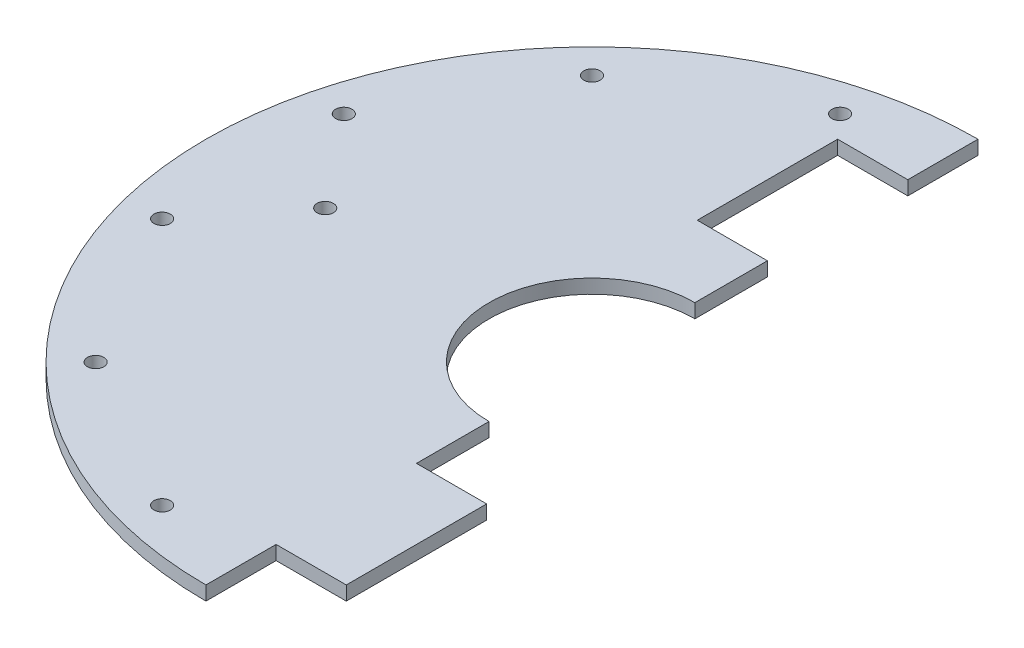
SolidWorks part; units mm, degrees
ref_plane "Front" through (0, 0, 0) normal (0, 0, 1) x (1, 0, 0)
ref_plane "Top" through (0, 0, 0) normal (0, 1, 0) x (1, 0, 0)
ref_plane "Right" through (0, 0, 0) normal (1, 0, 0) x (0, 0, -1)
sketch "Sketch1" plane through (0, 0, 0) normal (0, 1, 0) x (1, 0, 0)
  circle A0 centre (0, 0) radius 82.5
  dimension "D1" = 165
extrude "Boss-Extrude1" add sketch "Sketch1" along normal blind 3
sketch "Sketch2" plane through (0, 3, 0) normal (0, 1, 0) x (1, 0, 0)
  circle A0 centre (57, 0) radius 1.75
  circle A1 centre (0, 0) radius 22
  circle A2 centre (-57, 0) radius 1.75
  dimension "D1" = 3.5
  dimension "D2" = 44
  dimension "D4" = 3.5
  dimension "D3" = 57
  dimension "D5" = 57
extrude "Cut-Extrude1" cut sketch "Sketch2" against normal blind 3
sketch "Sketch3" plane through (0, 3, 0) normal (0, 1, 0) x (1, 0, 0)
  line L0 (0, 0) -> (90.6175, 0) construction
  circle A0 centre (72.4444, -19.4114) radius 1.75
  dimension "D2" = 3.5
  dimension "D1" = 75
  dimension "D3" = 15
extrude "Cut-Extrude2" cut sketch "Sketch3" against normal through all
pattern_circular "CirPattern1" count 12 over 360 about axis through (0, 0, 0) along (0, 1, 0) of "Cut-Extrude2"
sketch "Sketch4" plane through (0, 3, 0) normal (0, 1, 0) x (1, 0, 0)
  line L1 (0, 67.5) -> (-15, 67.5)
  line L2 (-15, 67.5) -> (-15, 37.5)
  line L3 (-15, 37.5) -> (0, 37.5)
  line L5 (0, -22) -> (0, -37.5)
  line L6 (0, -37.5) -> (15, -37.5)
  line L7 (15, -37.5) -> (15, -67.5)
  line L8 (15, -67.5) -> (0, -67.5)
  line L9 (0, -67.5) -> (0, -82.5)
  line L10 (0, 67.5) -> (0, 82.5)
  line L11 (0, 37.5) -> (0, 22)
  circle A0 centre (0, 0) radius 82.5 construction
  circle A1 centre (0, 0) radius 22 construction
  arc A4 (0, 22) -> (0, -22) centre (0, 0) cw
  arc A5 (0, 82.5) -> (0, -82.5) centre (0, 0) cw
  dimension "D1" = 15
  dimension "D5" = 22
  dimension "D2" = 30
  dimension "D3" = 30
  dimension "D4" = 15
  dimension "D6" = 15
  dimension "D7" = 15
  dimension "D8" = 15
extrude "Cut-Extrude3" cut sketch "Sketch4" against normal blind 3 contours L1 L2 L3 L11 A4 L5 L6 L7 L8 L9 A5 L10
